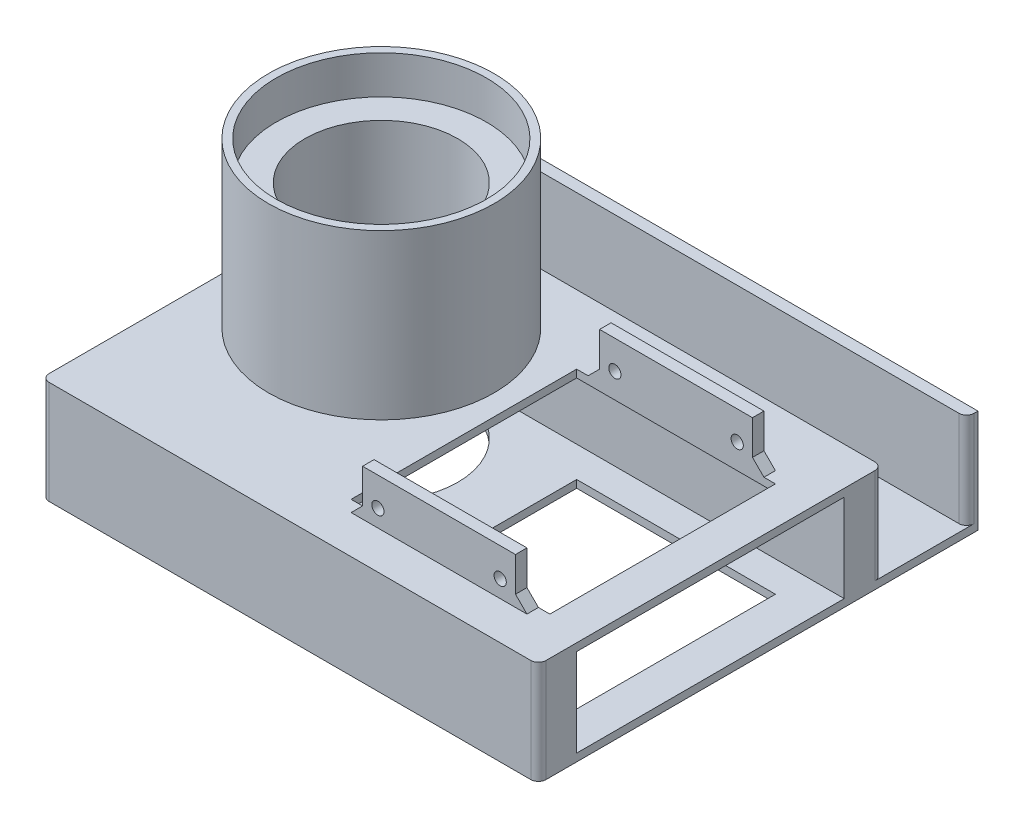
SolidWorks part; units mm, degrees
ref_plane "Front Plane" through (0, 0, 0) normal (0, 0, 1) x (1, 0, 0)
ref_plane "Top Plane" through (0, 0, 0) normal (0, 1, 0) x (1, 0, 0)
ref_plane "Right Plane" through (0, 0, 0) normal (1, 0, 0) x (0, 0, -1)
sketch "Sketch1" plane through (0, 0, 0) normal (0, 1, 0) x (1, 0, 0)
  circle A0 centre (0, 0) radius 29.5
  circle A1 centre (0, 0) radius 20
  dimension "D1" = 59
  dimension "D2" = 40
extrude "Boss-Extrude1" add sketch "Sketch1" along normal blind 42.88
sketch "Sketch2" plane through (0, 42.88, 0) normal (0, 1, 0) x (1, 0, 0)
  circle A0 centre (0, 0) radius 20
  circle A1 centre (0, 0) radius 27.5
  dimension "D1" = 40
  dimension "D2" = 55
extrude "Cut-Extrude1" cut sketch "Sketch2" against normal blind 10
sketch "Sketch3" plane through (0, 0, 0) normal (0, 1, 0) x (1, 0, 0)
  line L0 (0, 0) -> (60.9, 0) construction
  line L1 (60.9, 16) -> (60.9, 0) construction
  line L2 (40.9, 16) -> (80.9, 16)
  line L7 (40.9, 16) -> (40.9, -42.6)
  line L8 (40.9, -42.6) -> (80.9, -42.6)
  line L9 (80.9, 16) -> (80.9, -42.6)
  circle A0 centre (60.9, 0) radius 32.56
  dimension "D2" = 65.12
  dimension "D1" = 60.9
  dimension "D3" = 40
  dimension "D4" = 58.6
  dimension "D5" = 16
sketch "Sketch4" plane through (0, 0, 0) normal (0, 1, 0) x (1, 0, 0)
  line L0 (40.9, 16) -> (40.9, -42.6) construction
  line L1 (40.9, 16.2) -> (80.9, 16.2)
  line L2 (40.9, 16.2) -> (40.9, 19.2)
  line L3 (40.9, 19.2) -> (80.9, 19.2)
  line L4 (80.9, 16.2) -> (80.9, 19.2)
  line L5 (40.9, -42.8) -> (80.9, -42.8)
  line L6 (40.9, -42.8) -> (40.9, -45.8)
  line L7 (40.9, -45.8) -> (80.9, -45.8)
  line L8 (80.9, -42.8) -> (80.9, -45.8)
  line L9 (80.9, 16) -> (80.9, -42.6) construction
  line L10 (40.9, 16) -> (80.9, 16) construction
  line L11 (40.9, -42.6) -> (80.9, -42.6) construction
  dimension "D1" = 0.2
  dimension "D2" = 0.2
  dimension "D3" = 3
extrude "Boss-Extrude2" add sketch "Sketch4" along normal blind 12 separate body
sketch "Sketch5" plane through (0, 0, 45.8) normal (0, 0, 1) x (1, 0, 0)
  line L0 (40.9, 4.5) -> (80.9, 4.5) construction
  line L1 (40.9, 12) -> (40.9, 0) construction
  line L2 (80.9, 12) -> (80.9, 0) construction
  line L3 (93.46, 0) -> (28.34, 0) construction
  circle A0 centre (44.9, 4.5) radius 1.6
  circle A1 centre (76.9, 4.5) radius 1.6
  dimension "D2" = 4
  dimension "D3" = 4
  dimension "D4" = 3.2
  dimension "D1" = 4.5
extrude "Cut-Extrude2" cut sketch "Sketch5" against normal up to surface (65 mm away)
sketch "Sketch6" plane through (0, 0, 0) normal (0, 1, 0) x (1, 0, 0)
  line L1 (-33.1, -55.8) -> (96.9, -55.8)
  line L2 (96.9, -55.8) -> (96.9, 34.2)
  line L3 (96.9, 34.2) -> (-33.1, 34.2)
  line L5 (34.9, -42.8) -> (86.9, -42.8)
  line L6 (34.9, -42.8) -> (34.9, 16.2)
  line L7 (34.9, 16.2) -> (86.9, 16.2)
  line L8 (86.9, -42.8) -> (86.9, 16.2)
  line L10 (40.9, 16) -> (40.9, -42.6) construction
  line L11 (80.9, 16) -> (80.9, -42.6) construction
  line L12 (40.9, -45.8) -> (80.9, -45.8) construction
  line L13 (-33.1, 34.2) -> (-33.1, -55.8)
  line L14 (40.9, 16.2) -> (80.9, 16.2) construction
  line L15 (80.9, -42.8) -> (40.9, -42.8) construction
  circle A2 centre (0, 0) radius 20
  dimension "D3" = 10
  dimension "D4" = 40
  dimension "D1" = 6
  dimension "D2" = 6
  dimension "D5" = 130
  dimension "D6" = 90
  dimension "D7" = 10
extrude "Boss-Extrude3" add sketch "Sketch6" against normal blind 2
sketch "Sketch8" plane through (0, -2, 0) normal (0, -1, 0) x (1, 0, 0)
  line L0 (96.9, 55.8) -> (96.9, -34.2) construction
  line L1 (-33.1, 55.8) -> (96.9, 55.8)
  line L2 (-33.1, 55.8) -> (-33.1, 45.8)
  line L3 (-33.1, 45.8) -> (96.9, 45.8)
  line L4 (96.9, 55.8) -> (96.9, 45.8)
  line L6 (-33.1, -34.2) -> (96.9, -34.2)
  line L7 (-33.1, -34.2) -> (-33.1, -24.2)
  line L8 (-33.1, -24.2) -> (96.9, -24.2)
  line L9 (96.9, -34.2) -> (96.9, -24.2)
  dimension "D1" = 70
extrude "Boss-Extrude4" add sketch "Sketch8" along normal blind 23
sketch "Sketch9" plane through (0, -25, 0) normal (0, -1, 0) x (1, 0, 0)
  line L1 (-33.1, 55.8) -> (96.9, 55.8)
  line L2 (-33.1, 55.8) -> (-33.1, -34.2)
  line L3 (-33.1, -34.2) -> (96.9, -34.2)
  line L4 (96.9, 55.8) -> (96.9, -34.2)
  line L5 (34.9, 42.8) -> (86.9, 42.8)
  line L6 (34.9, 42.8) -> (34.9, -16.2)
  line L7 (34.9, -16.2) -> (86.9, -16.2)
  line L8 (86.9, 42.8) -> (86.9, -16.2)
  circle A0 centre (0, 0) radius 20
  circle A1 centre (0, 0) radius 20 construction
extrude "Boss-Extrude5" add sketch "Sketch9" along normal blind 2
chamfer "Chamfer1" distance 3 angle 45 4 edges at (40.9, 0, -17.7) (80.9, 0, -17.7) (40.9, 0, 44.3) (80.9, 0, 44.3)
sketch "Sketch11" plane through (96.9, 0, 0) normal (1, 0, 0) x (0, 0, -1)
  line L0 (34.2, -27) -> (34.2, -25)
  line L1 (34.2, -27) -> (34.2, 0) construction
  line L2 (34.2, -25) -> (56.2, -25)
  line L3 (56.2, -25) -> (56.2, 0)
  line L4 (56.2, 0) -> (59.2, 0)
  line L5 (59.2, 0) -> (59.2, -27)
  line L6 (59.2, -27) -> (34.2, -27)
  line L7 (-55.8, 0) -> (34.2, 0) construction
  dimension "D1" = 2
  dimension "D2" = 3
  dimension "D3" = 22
extrude "Boss-Extrude6" add sketch "Sketch11" against normal up to surface (130 mm away) up to face at (-33.1, -13.5, 10.8)
fillet "Fillet1" radius 2 6 edges at (96.9, -12.5, -34.2) (96.9, -13.5, 55.8) (-33.1, -12.5, -34.2) (-33.1, -13.5, 55.8) (-33.1, -12.5, -56.2) (96.9, -12.5, -56.2)
